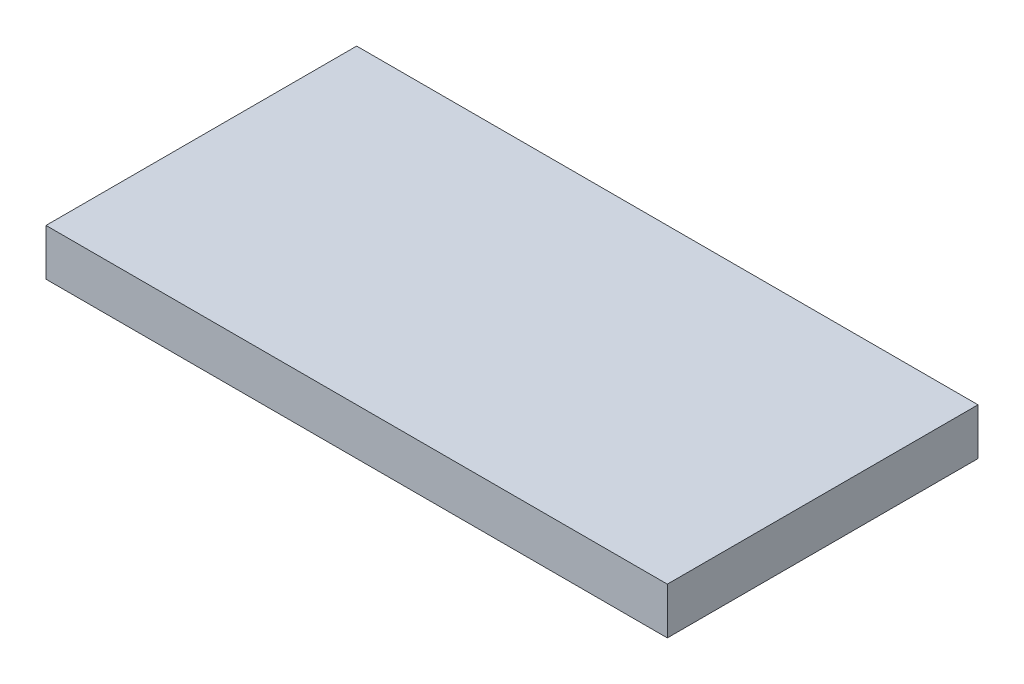
SolidWorks part; units mm, degrees
ref_plane "Front Plane" through (0, 0, 0) normal (0, 0, 1) x (1, 0, 0)
ref_plane "Top Plane" through (0, 0, 0) normal (0, 1, 0) x (1, 0, 0)
ref_plane "Right Plane" through (0, 0, 0) normal (1, 0, 0) x (0, 0, -1)
sketch "Sketch1" plane through (0, 0, 0) normal (0, 1, 0) x (1, 0, 0)
  line L1 (-40, -20) -> (40, -20)
  line L2 (-40, -20) -> (-40, 20)
  line L3 (-40, 20) -> (40, 20)
  line L4 (40, -20) -> (40, 20)
  line L5 (-40, -20) -> (40, 20) construction
  line L6 (-40, 20) -> (40, -20) construction
  point P0 (0, 0)
  dimension "D1" = 80
  dimension "D2" = 40
extrude "Boss-Extrude1" add sketch "Sketch1" along normal blind 6
